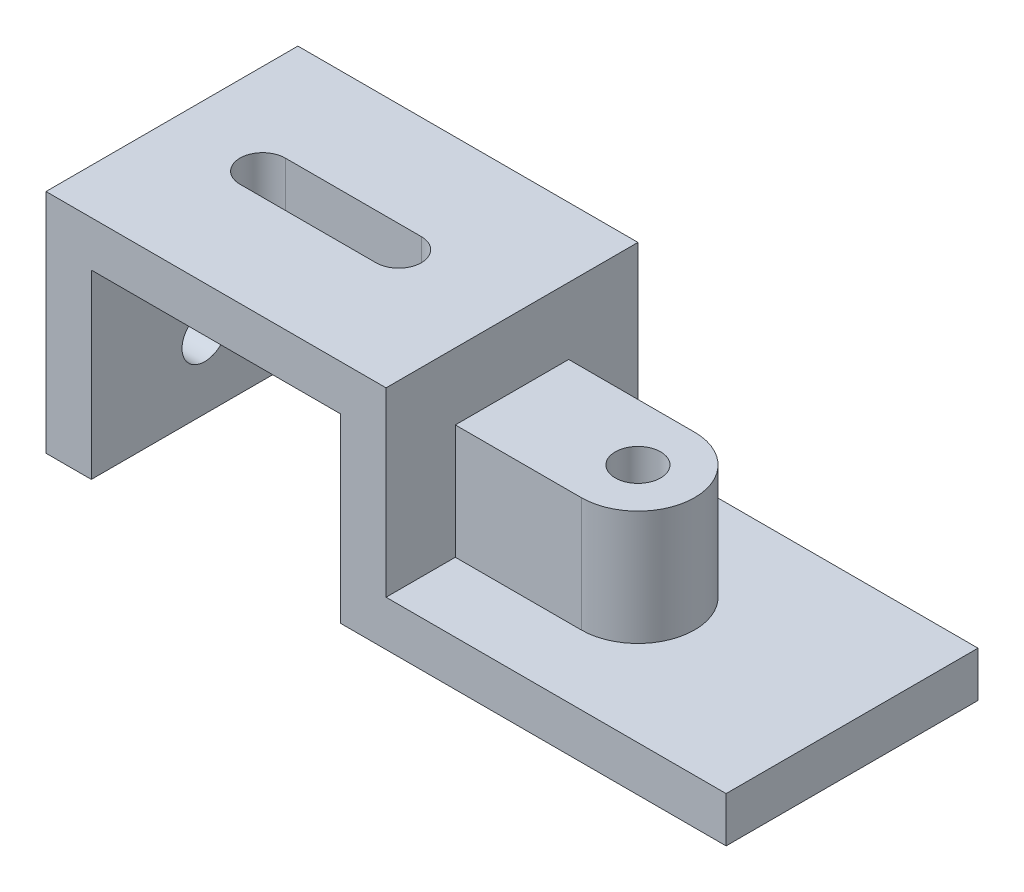
SolidWorks part; units mm, degrees
ref_plane "Front Plane" through (0, 0, 0) normal (0, 0, 1) x (1, 0, 0)
ref_plane "Top Plane" through (0, 0, 0) normal (0, 1, 0) x (1, 0, 0)
ref_plane "Right Plane" through (0, 0, 0) normal (1, 0, 0) x (0, 0, -1)
sketch "Sketch1" plane through (0, 0, 0) normal (0, 0, 1) x (1, 0, 0)
  line L0 (0, 0) -> (0, 90)
  line L1 (0, 90) -> (135, 90)
  line L2 (135, 90) -> (135, 18)
  line L3 (135, 18) -> (270, 18)
  line L4 (270, 18) -> (270, 0)
  line L5 (270, 0) -> (117, 0)
  line L6 (117, 0) -> (117, 72)
  line L7 (117, 72) -> (18, 72)
  line L8 (18, 72) -> (18, 0)
  line L9 (18, 0) -> (0, 0)
  dimension "D1" = 18
  dimension "D2" = 18
  dimension "D3" = 135
  dimension "D4" = 99
  dimension "D5" = 18
  dimension "D6" = 90
  dimension "D7" = 135
extrude "Boss-Extrude1" add sketch "Sketch1" along normal blind 100
sketch "Sketch2" plane through (0, 90, 0) normal (0, 1, 0) x (1, 0, 0)
  line L0 (36, -50) -> (90, -50) construction
  line L1 (36, -41) -> (90, -41)
  line L2 (36, -59) -> (90, -59)
  line L3 (0, -100) -> (0, 0) construction
  line L5 (0, -50) -> (285.432, -50) construction
  arc A0 (36, -41) -> (36, -59) centre (36, -50) ccw
  arc A1 (90, -59) -> (90, -41) centre (90, -50) ccw
  point P2 (63, -50)
  dimension "D1" = 18
  dimension "D2" = 36
  dimension "D4" = 54
extrude "Cut-Extrude1" cut sketch "Sketch2" against normal blind 100
sketch "Sketch4" plane through (0, 18, 0) normal (0, 1, 0) x (1, 0, 0)
  line L0 (135, -50) -> (300.0216, -50) construction
  line L2 (185, -27.5) -> (135, -27.5)
  line L3 (185, -72.5) -> (135, -72.5)
  line L4 (135, -100) -> (135, 0) construction
  line L5 (135, -72.5) -> (135, -27.5)
  line L6 (0, -50) -> (135, -50) construction
  line L7 (0, -100) -> (0, 0) construction
  arc A0 (185, -72.5) -> (185, -27.5) centre (185, -50) ccw
  dimension "D1" = 22.5
  dimension "D2" = 50
extrude "Boss-Extrude2" add sketch "Sketch4" along normal blind 45.5
hole_wizard "Hole1" positions "Sketch5" profile "Sketch6" legacy end condition up to next
sketch "Sketch5" plane through (0, 63.5, 0) normal (0, 1, 0) x (1, 0, 0)
  point P0 (185, -50)
sketch "Sketch6" plane through (185, 63.5, 50) normal (1, 0, 0) x (0, 0, 1)
  line L0 (0, 0) -> (0, 63.5)
  line L1 (0, 63.5) -> (9, 63.5)
  line L2 (9, 63.5) -> (9, 0)
  line L3 (9, 0) -> (0, 0)
  line L4 (0, 110) -> (0, -10) construction
  dimension "Diameter" = 18
  dimension "Depth" = 63.5
hole_wizard "Hole2" positions "Sketch7" profile "Sketch8" legacy
sketch "Sketch7" plane through (0, 0, 0) normal (-1, 0, 0) x (0, 0, 1)
  line L0 (100, 0) -> (0, 0) construction
  line L2 (100, 90) -> (100, 0) construction
  point P0 (55, 27)
  dimension "D1" = 27
  dimension "D2" = 45
sketch "Sketch8" plane through (0, 27, 55) normal (0, 1, 0) x (0, 0, 1)
  line L0 (0, 0) -> (0, 18)
  line L1 (0, 18) -> (9, 18)
  line L2 (9, 18) -> (9, 0)
  line L3 (9, 0) -> (0, 0)
  line L4 (0, 110) -> (0, -10) construction
  dimension "Diameter" = 18
  dimension "Depth" = 18
